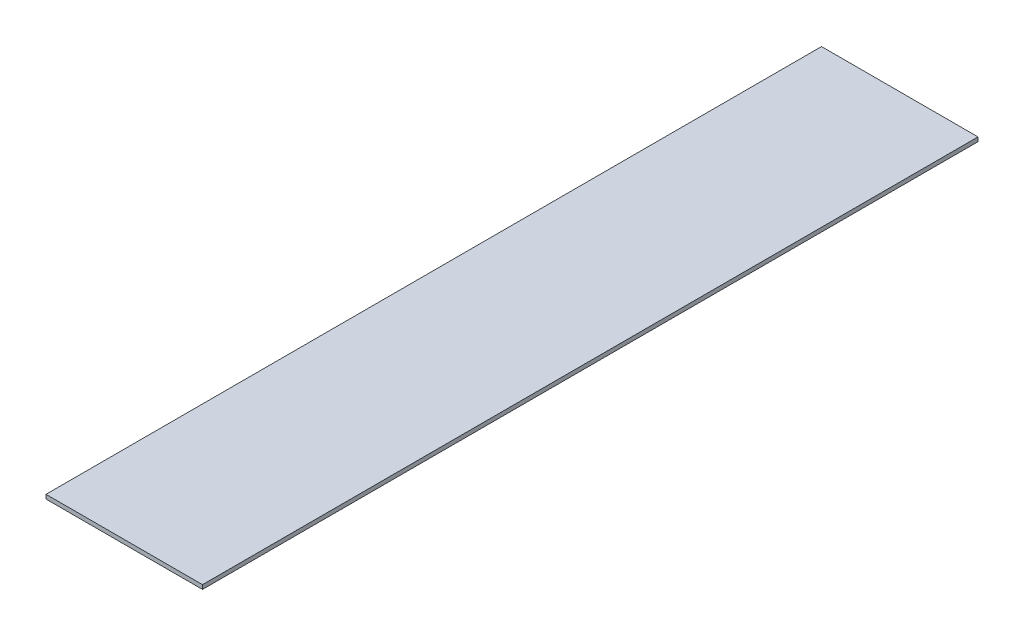
SolidWorks part; units mm, degrees
material "CA"
ref_plane "Front Plane" through (0, 0, 0) normal (0, 0, 1) x (1, 0, 0)
ref_plane "Top Plane" through (0, 0, 0) normal (0, 1, 0) x (1, 0, 0)
ref_plane "Right Plane" through (0, 0, 0) normal (1, 0, 0) x (0, 0, -1)
sketch "Sketch1" plane through (0, 0, 0) normal (0, 1, 0) x (1, 0, 0)
  line L1 (0, 0) -> (113, 0)
  line L2 (0, 0) -> (0, 560)
  line L3 (0, 560) -> (113, 560)
  line L4 (113, 0) -> (113, 560)
  dimension "D1" = 113
  dimension "D2" = 560
extrude "Boss-Extrude1" add sketch "Sketch1" along normal blind 3
